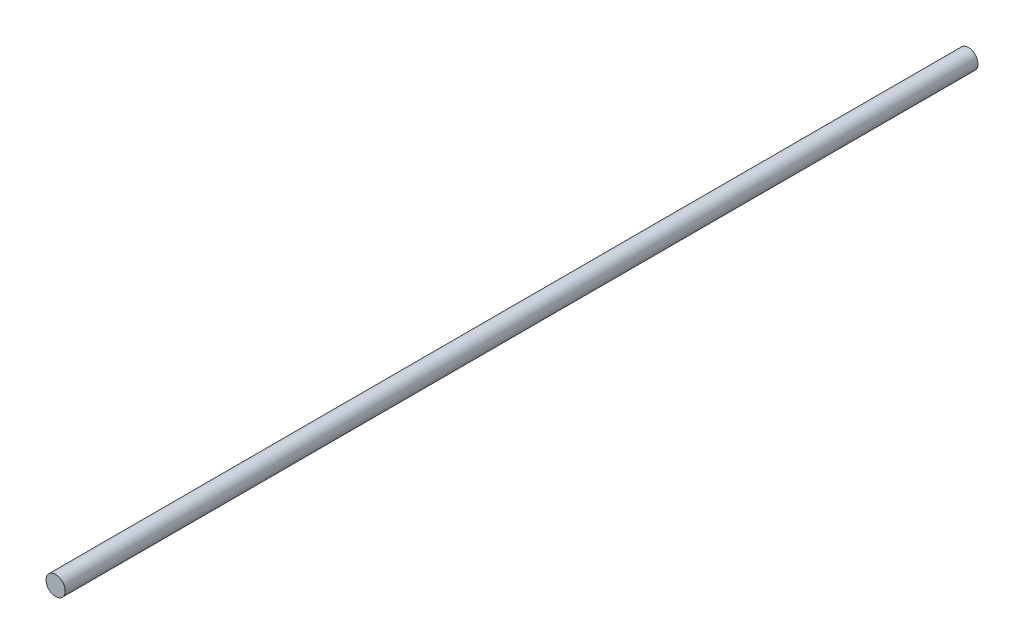
SolidWorks part; units mm, degrees
ref_plane "Спереди" through (0, 0, 0) normal (0, 0, 1) x (1, 0, 0)
ref_plane "Сверху" through (0, 0, 0) normal (0, 1, 0) x (1, 0, 0)
ref_plane "Справа" through (0, 0, 0) normal (1, 0, 0) x (0, 0, -1)
sketch "Эскиз1" plane through (0, 0, 0) normal (0, 0, 1) x (1, 0, 0)
  circle A0 centre (0, 0) radius 4
  dimension "D1" = 8
extrude "Бобышка-Вытянуть1" add sketch "Эскиз1" along normal blind 380
